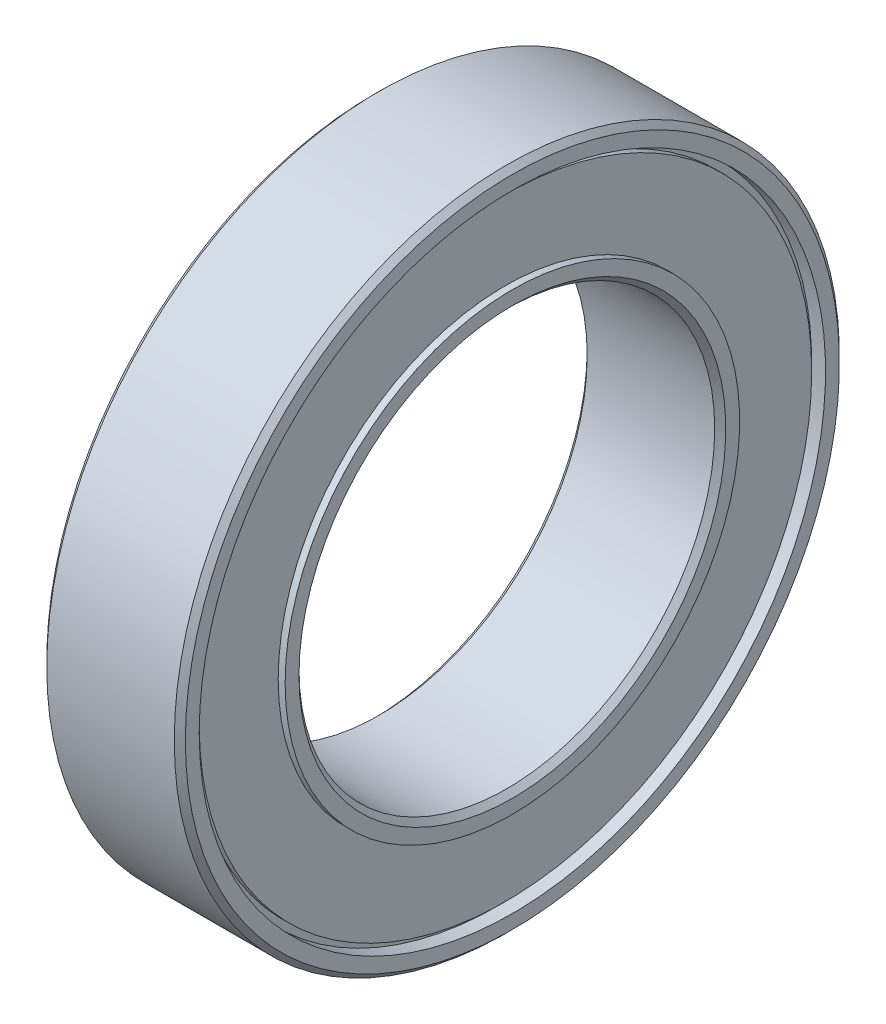
SolidWorks part; units mm, degrees
ref_plane "前视基准面" through (0, 0, 0) normal (0, 0, 1) x (1, 0, 0)
ref_plane "上视基准面" through (0, 0, 0) normal (0, 1, 0) x (1, 0, 0)
ref_plane "右视基准面" through (0, 0, 0) normal (1, 0, 0) x (0, 0, -1)
other "Configuration Table"
sketch "草图1" plane through (0, 0, 0) normal (0, 0, 1) x (1, 0, 0)
  line L0 (-3.901, 0) -> (3.7973, 0) construction
  line L1 (0, 7.17) -> (0, -5.7744) construction
  line L2 (-2.5, 7.5) -> (2.5, 7.5)
  line L3 (2.5, 7.5) -> (2.5, 8.2)
  line L4 (2.5, 8.2) -> (2.25, 8.2)
  line L5 (2.25, 8.2) -> (2.25, 11.05)
  line L6 (2.25, 11.05) -> (2, 11.05)
  line L7 (2, 11.05) -> (2, 11.3)
  line L8 (2, 11.3) -> (2.5, 11.3)
  line L9 (2.5, 11.3) -> (2.5, 12)
  line L10 (2.5, 12) -> (-2.5, 12)
  line L11 (-2.5, 11.3) -> (-2.5, 12)
  line L12 (-2, 11.3) -> (-2.5, 11.3)
  line L13 (-2, 11.05) -> (-2, 11.3)
  line L14 (-2.25, 11.05) -> (-2, 11.05)
  line L15 (-2.25, 8.2) -> (-2.25, 11.05)
  line L16 (-2.5, 8.2) -> (-2.25, 8.2)
  line L17 (-2.5, 7.5) -> (-2.5, 8.2)
  point P6 (-2.5, 7.85)
  point P16 (0, 12)
  point P23 (0, 7.5)
  dimension "D1" = 7.5
  dimension "D2" = 0.7
  dimension "D3" = 12
  dimension "D4" = 0.7
  dimension "D5" = 0.25
  dimension "D6" = 5
  dimension "D7" = 0.25
  dimension "D8" = 0.5
revolve "旋转1" add sketch "草图1" angle 360 about L0
chamfer "倒角1" distance 0.2 angle 45 4 edges at (2.5, 0, 12) (-2.5, 0, 12) (-2.5, 0, 7.5) (2.5, 0, 7.5)
